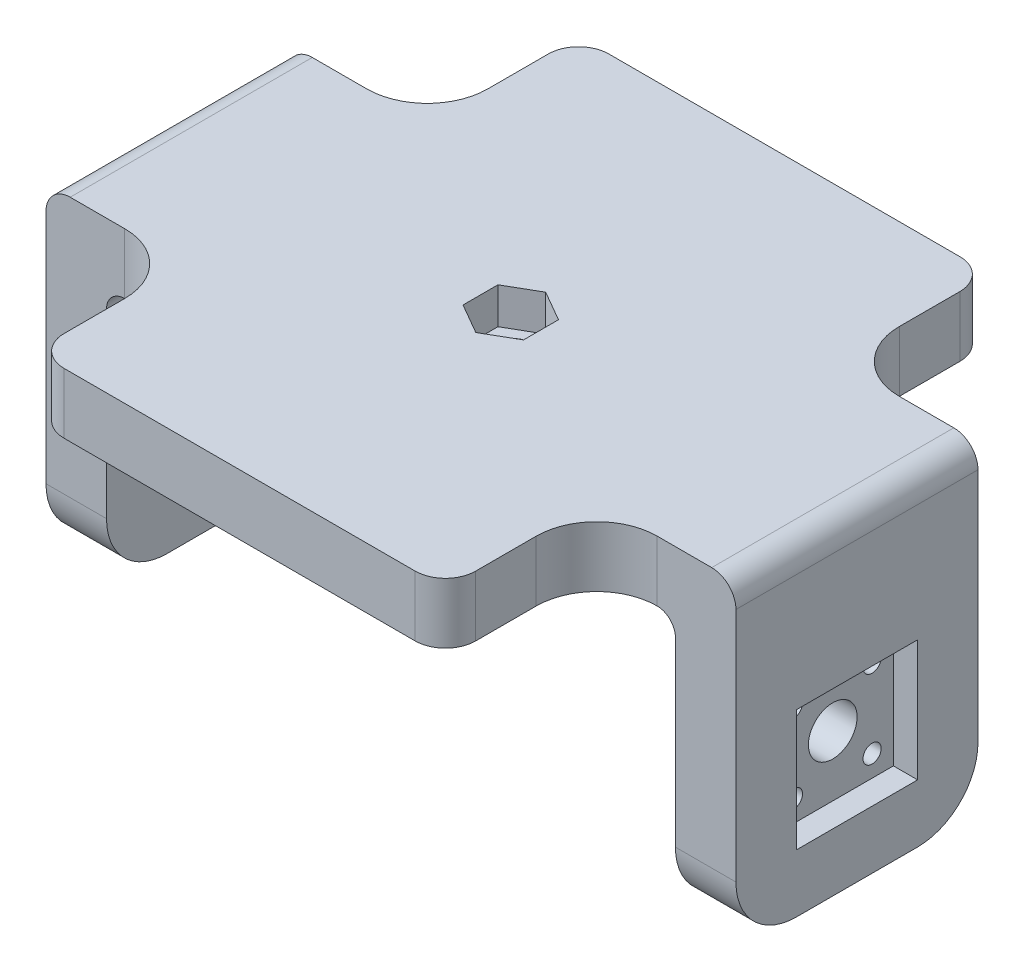
SolidWorks part; units mm, degrees
ref_plane "Front Plane" through (0, 0, 0) normal (0, 0, 1) x (1, 0, 0)
ref_plane "Top Plane" through (0, 0, 0) normal (0, 1, 0) x (1, 0, 0)
ref_plane "Right Plane" through (0, 0, 0) normal (1, 0, 0) x (0, 0, -1)
sketch "Sketch1" plane through (0, 0, 0) normal (0, 0, 1) x (1, 0, 0)
  line L0 (10, 0) -> (10, 43)
  line L1 (0, 0) -> (10, 0)
  line L2 (0, 0) -> (0, 53)
  line L3 (0, 53) -> (114, 53)
  line L4 (114, 0) -> (114, 53)
  line L5 (10, 43) -> (104, 43)
  line L6 (104, 43) -> (104, 0)
  line L7 (104, 0) -> (114, 0)
  dimension "D1" = 94
  dimension "D2" = 43
  dimension "D3" = 10
  dimension "D4" = 10
  dimension "D5" = 53
extrude "Boss-Extrude1" add sketch "Sketch1" against normal blind 40
sketch "Sketch2" plane through (10, 0, 0) normal (1, 0, 0) x (0, 0, -1)
  line L0 (5, 4.6351) -> (5, 34.6351) construction
  line L1 (5, 4.6351) -> (35, 4.6351) construction
  line L2 (5, 34.6351) -> (35, 34.6351) construction
  line L3 (35, 4.6351) -> (35, 34.6351) construction
  line L5 (5, 4.6351) -> (35, 34.6351) construction
  line L6 (5, 34.6351) -> (35, 4.6351) construction
  circle A0 centre (20, 19.6351) radius 12.5
  point P0 (20, 19.6351)
  dimension "D4" = 4.6351
  dimension "D1" = 30
  dimension "D2" = 30
  dimension "D3" = 20
extrude "Cut-Extrude1" cut sketch "Sketch2" against normal blind 4.4775
fillet "Fillet1" radius 10 4 edges at (109, 0, -40) (109, 0, 0) (5, 0, -40) (5, 0, 0)
sketch "Sketch4" plane through (7.725, 0, 0) normal (1, 0, 0) x (0, 0, -1)
  circle A0 centre (20, 19.6351) radius 2.5
  dimension "D1" = 5
extrude "Cut-Extrude2" cut sketch "Sketch4" against normal blind 14.2 and the other way blind 131.2
sketch "Sketch6" plane through (0, 53, 0) normal (0, 1, 0) x (1, 0, 0)
  line L1 (23, -25) -> (91, -25)
  line L2 (23, -25) -> (23, 65)
  line L3 (23, 65) -> (91, 65)
  line L4 (91, -25) -> (91, 65)
  line L5 (23, -25) -> (91, 65) construction
  line L6 (23, 65) -> (91, -25) construction
  line L7 (114, 40) -> (0, 40) construction
  point P0 (57, 20)
  dimension "D1" = 90
  dimension "D2" = 68
  dimension "D3" = 57
  dimension "D4" = 20
extrude "Boss-Extrude4" add sketch "Sketch6" against normal blind 10
fillet "Fillet2" radius 10 4 edges at (91, 48, -40) (91, 48, 0) (23, 48, -40) (23, 48, 0)
fillet "Fillet3" radius 5 4 edges at (91, 48, 25) (23, 48, 25) (23, 48, -65) (91, 48, -65)
fillet "Fillet4" radius 4 2 edges at (114, 53, -20) (0, 53, -20)
sketch "Sketch7" plane through (7.725, 0, 0) normal (1, 0, 0) x (0, 0, -1)
  circle A0 centre (20, 19.6351) radius 3.9
  dimension "D1" = 7.8
extrude "Cut-Extrude3" cut sketch "Sketch7" against normal blind 0.85 from surface at -2.2025 starting at face at (5.5225, 19.6351, -32.5)
sketch "Sketch8" plane through (0, 53, 0) normal (0, 1, 0) x (1, 0, 0)
  line L0 (114, 40) -> (114, 0) construction
  line L1 (28, -25) -> (86, -25) construction
  circle A0 centre (57, 20) radius 3.25
  dimension "D3" = 6.5
  dimension "D1" = 57
  dimension "D2" = 45
extrude "Cut-Extrude4" cut sketch "Sketch8" against normal blind 10
sketch "Sketch9" plane through (114, 0, 0) normal (1, 0, 0) x (0, 0, -1)
  circle A0 centre (20, 19.6351) radius 4.025
  dimension "D1" = 8.05
extrude "Cut-Extrude5" cut sketch "Sketch9" against normal blind 12
sketch "Sketch10" plane through (114, 0, 0) normal (1, 0, 0) x (0, 0, -1)
  line L1 (9.975, 9.6101) -> (30.025, 9.6101)
  line L2 (9.975, 9.6101) -> (9.975, 29.6601)
  line L3 (9.975, 29.6601) -> (30.025, 29.6601)
  line L4 (30.025, 9.6101) -> (30.025, 29.6601)
  line L5 (9.975, 9.6101) -> (30.025, 29.6601) construction
  line L6 (9.975, 29.6601) -> (30.025, 9.6101) construction
  point P0 (20, 19.6351)
  dimension "D1" = 20.05
  dimension "D2" = 20.05
extrude "Cut-Extrude6" cut sketch "Sketch10" against normal blind 4
sketch "Sketch14" plane through (0, 53, 0) normal (0, 1, 0) x (1, 0, 0)
  line L0 (56.8729, 25.695) -> (61.8729, 22.8082)
  line L1 (61.8729, 22.8082) -> (61.8729, 17.0347)
  line L2 (61.8729, 17.0347) -> (56.8729, 14.148)
  line L3 (56.8729, 14.148) -> (51.8729, 17.0347)
  line L4 (51.8729, 17.0347) -> (51.8729, 22.8082)
  line L5 (51.8729, 22.8082) -> (56.8729, 25.695)
extrude "Cut-Extrude7" cut sketch "Sketch14" against normal blind 6 contours L2 L3 L4 L5 L0 L1
sketch "Sketch15" plane through (104, 0, 0) normal (-1, 0, 0) x (0, 0, 1)
  circle A0 centre (-26.5, 26.1351) radius 1.5
  circle A1 centre (-13.5, 26.1351) radius 1.5
  circle A2 centre (-13.5, 13.1351) radius 1.5
  circle A3 centre (-26.5, 13.1351) radius 1.5
  circle A4 centre (-13.4008, 24.6117) radius 0.0267
sketch "Sketch18" plane through (104, 0, 0) normal (-1, 0, 0) x (0, 0, 1)
  line L0 (-13.429, 23.2499) -> (-11.8413, 23.2499) construction
  line L1 (-15.0489, 28.9136) -> (-11.9101, 28.9136)
  line L3 (-15.151, 23.2499) -> (-11.8916, 23.2499)
  line L5 (-15.0489, 28.9136) -> (-11.8916, 23.2499) construction
  line L6 (-15.151, 23.2499) -> (-11.9101, 28.9136) construction
  line L7 (-13.4702, 26.0817) -> (-10.2705, 26.0817) construction
  line L8 (-10.2705, 26.0817) -> (-13.4702, 26.0817) construction
  line L9 (-13.4702, 26.0817) -> (-16.734, 26.0817) construction
  line L10 (-16.734, 26.0817) -> (-15.0489, 28.9136)
  line L11 (-11.9101, 28.9136) -> (-10.2705, 26.0817)
  line L12 (-10.2705, 26.0817) -> (-11.8916, 23.2499)
  line L13 (-15.151, 23.2499) -> (-16.734, 26.0817)
  line L14 (-13.5, 13.1351) -> (-26.5, 13.1351) construction
  line L15 (-26.5, 13.1351) -> (-20, 13.1351) construction
  line L16 (-20, 13.1351) -> (-20, 32.3861) construction
  line L17 (-20, 32.3861) -> (-20, 19.6351) construction
  line L18 (-20, 19.6351) -> (-8.7366, 19.6351) construction
  line L19 (-8.7366, 19.6351) -> (-30.7611, 19.6351) construction
  line L20 (-23.266, 26.0817) -> (-24.9511, 28.9136)
  line L21 (-24.849, 23.2499) -> (-23.266, 26.0817)
  line L22 (-24.849, 23.2499) -> (-28.1084, 23.2499)
  line L23 (-29.7295, 26.0817) -> (-28.1084, 23.2499)
  line L24 (-28.0899, 28.9136) -> (-29.7295, 26.0817)
  line L25 (-24.9511, 28.9136) -> (-28.0899, 28.9136)
  line L26 (-16.734, 13.1886) -> (-15.0489, 10.3567)
  line L27 (-15.151, 16.0204) -> (-16.734, 13.1886)
  line L28 (-15.151, 16.0204) -> (-11.8916, 16.0204)
  line L29 (-10.2705, 13.1886) -> (-11.8916, 16.0204)
  line L30 (-11.9101, 10.3567) -> (-10.2705, 13.1886)
  line L31 (-15.0489, 10.3567) -> (-11.9101, 10.3567)
  line L32 (-24.849, 16.0204) -> (-23.266, 13.1886)
  line L33 (-24.849, 16.0204) -> (-28.1084, 16.0204)
  line L34 (-29.7295, 13.1886) -> (-28.1084, 16.0204)
  line L35 (-28.0899, 10.3567) -> (-29.7295, 13.1886)
  line L36 (-24.9511, 10.3567) -> (-28.0899, 10.3567)
  line L37 (-23.266, 13.1886) -> (-24.9511, 10.3567)
  point P0 (-13.5, 26.1351)
extrude "Cut-Extrude9" cut sketch "Sketch18" against normal blind 2.5
extrude "Cut-Extrude10" cut sketch "Sketch15" against normal up to next from offset 2.5 contours A0 | A3 | A2 | A1 offset against normal yes
fillet "Fillet5" radius 3 2 edges at (104, 43, -20) (10, 43, -20)
